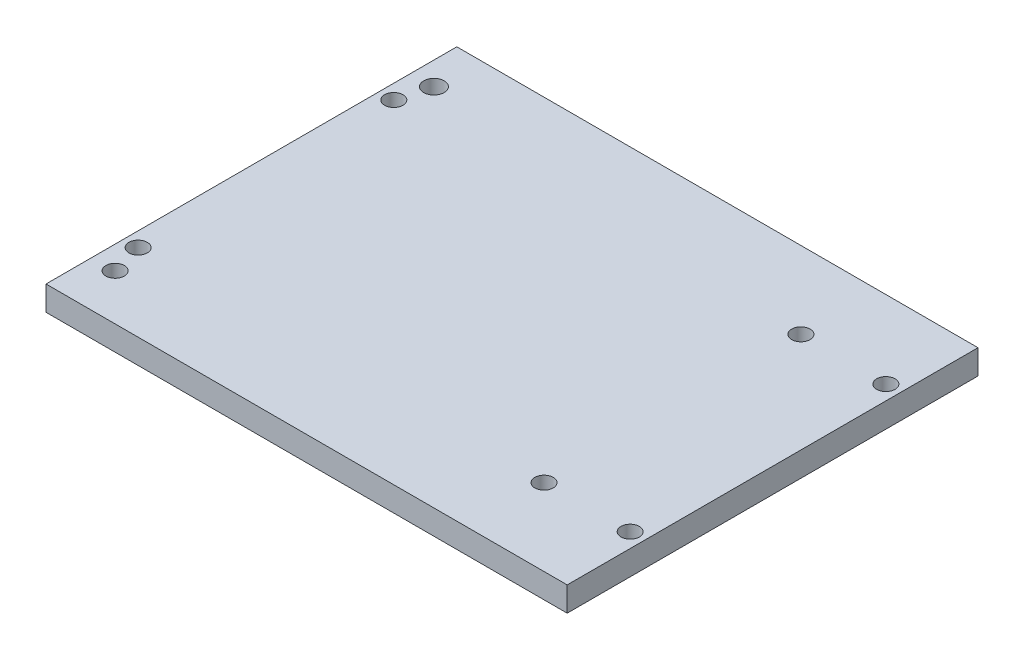
SolidWorks part; units mm, degrees
ref_plane "Front Plane" through (0, 0, 0) normal (0, 0, 1) x (1, 0, 0)
ref_plane "Top Plane" through (0, 0, 0) normal (0, 1, 0) x (1, 0, 0)
ref_plane "Right Plane" through (0, 0, 0) normal (1, 0, 0) x (0, 0, -1)
sketch "Sketch1" plane through (0, 0, 0) normal (0, 1, 0) x (1, 0, 0)
  line L1 (-42.5, 33.5) -> (42.5, 33.5)
  line L2 (-42.5, 33.5) -> (-42.5, -33.5)
  line L3 (-42.5, -33.5) -> (42.5, -33.5)
  line L4 (42.5, 33.5) -> (42.5, -33.5)
  line L5 (-42.5, 33.5) -> (42.5, -33.5) construction
  line L6 (-42.5, -33.5) -> (42.5, 33.5) construction
  point P0 (0, 0)
  dimension "D1" = 67
  dimension "D2" = 85
extrude "Boss-Extrude1" add sketch "Sketch1" along normal blind 4
sketch "Sketch2" plane through (0, 4, 0) normal (0, 1, 0) x (1, 0, 0)
  line L0 (-37.75, 33.5) -> (-37.75, -33.5) construction
  line L1 (42.5, 33.5) -> (-42.5, 33.5) construction
  line L2 (-42.5, -33.5) -> (42.5, -33.5) construction
  line L3 (37.75, 33.5) -> (37.75, -33.5) construction
  line L4 (-42.5, 33.5) -> (-42.5, -33.5) construction
  line L5 (42.5, -33.5) -> (42.5, 33.5) construction
  line L6 (-42.5, 20.85) -> (42.5, 20.85) construction
  line L7 (-42.5, -20.85) -> (42.5, -20.85) construction
  line L8 (-42.5, 0) -> (-37.75, 0) construction
  line L9 (-40.125, 0) -> (-40.125, 20.85) construction
  line L10 (-40.125, 0) -> (-40.125, -20.85) construction
  line L11 (-37.75, 0) -> (37.75, 0) construction
  line L12 (37.75, 0) -> (42.5, 0) construction
  line L13 (40.125, 0) -> (40.125, 20.85) construction
  line L14 (40.125, 0) -> (40.125, -20.85) construction
  circle A0 centre (-40.125, 20.85) radius 1.5
  circle A1 centre (-40.125, -20.85) radius 1.5
  circle A2 centre (40.125, 20.85) radius 1.5
  circle A3 centre (40.125, -20.85) radius 1.5
  dimension "D1" = 4.75
  dimension "D2" = 4.75
  dimension "D3" = 12.65
  dimension "D4" = 12.65
extrude "Cut-Extrude1" cut sketch "Sketch2" against normal blind 4
sketch "Sketch3" plane through (0, 4, 0) normal (0, 1, 0) x (1, 0, 0)
  line L0 (42.5, 33.5) -> (-42.5, 33.5) construction
  line L1 (40.4, 33.5) -> (40.4, -33.5) construction
  line L2 (-42.5, -33.5) -> (42.5, -33.5) construction
  line L3 (-40.4, 33.5) -> (-40.4, -33.5) construction
  line L4 (42.5, -33.5) -> (42.5, 33.5) construction
  line L5 (-42.5, 33.5) -> (-42.5, -33.5) construction
  line L6 (42.5, 28.85) -> (-42.5, 28.85) construction
  line L7 (42.5, -28.85) -> (-42.5, -28.85) construction
  line L8 (-38.73, 28.85) -> (-38.73, -28.85) construction
  circle A0 centre (26.1732, 20.95) radius 1.5
  circle A1 centre (26.1732, -20.95) radius 1.5
  circle A2 centre (-38.73, 26) radius 1.67
  circle A3 centre (-38.73, -26) radius 1.5
  dimension "D7" = 1.67
  dimension "D8" = 2.85
  dimension "D9" = 2.85
  dimension "D1" = 2.1
  dimension "D2" = 2.1
  dimension "D3" = 4.65
  dimension "D4" = 4.65
  dimension "D5" = 7.9
  dimension "D6" = 7.9
extrude "Cut-Extrude2" cut sketch "Sketch3" against normal blind 10
